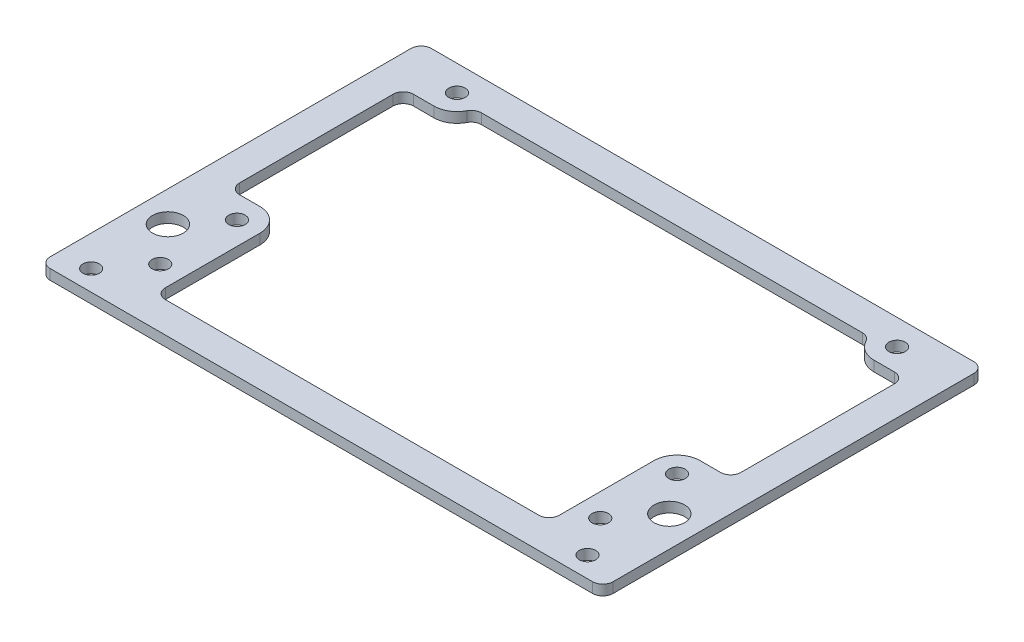
SolidWorks part; units mm, degrees
material "Thornel Mat VMA"
ref_plane "前视基准面" through (0, 0, 0) normal (0, 0, 1) x (1, 0, 0)
ref_plane "上视基准面" through (0, 0, 0) normal (0, 1, 0) x (1, 0, 0)
ref_plane "右视基准面" through (0, 0, 0) normal (1, 0, 0) x (0, 0, -1)
other "Configuration Table"
sketch "草图1" plane through (0, 0, 0) normal (0, 1, 0) x (1, 0, 0)
  line L1 (-43, 29) -> (43, 29) construction
  line L2 (-43, 29) -> (-43, -29) construction
  line L3 (-43, -29) -> (43, -29) construction
  line L4 (43, 29) -> (43, -29) construction
  line L5 (-43, 29) -> (43, -29) construction
  line L6 (-43, -29) -> (43, 29) construction
  line L7 (-55, 39.5) -> (55, 39.5)
  line L8 (-55, 39.5) -> (-55, -39.5)
  line L9 (-55, -39.5) -> (55, -39.5)
  line L10 (55, 39.5) -> (55, -39.5)
  line L11 (-55, 39.5) -> (55, -39.5) construction
  line L12 (-55, -39.5) -> (55, 39.5) construction
  circle A0 centre (43, -29) radius 1.6
  circle A1 centre (-43, -29) radius 1.6
  circle A2 centre (-43, 29) radius 1.6
  circle A3 centre (43, 29) radius 1.6
  circle A4 centre (43, -14) radius 1.6
  circle A5 centre (-43, -14) radius 1.6
  point P0 (0, 0)
  point P10 (0, 0)
  dimension "D3" = 3.2
  dimension "D1" = 86
  dimension "D2" = 58
  dimension "D4" = 110
  dimension "D5" = 79
  dimension "D6" = 43
extrude "凸台-拉伸1" add sketch "草图1" along normal blind 2
sketch "草图3" plane through (0, 2, 0) normal (0, 1, 0) x (1, 0, 0)
  line L1 (-55, -39.5) -> (55, -39.5)
  line L2 (-55, -39.5) -> (-55, -40.5)
  line L3 (-55, -40.5) -> (55, -40.5)
  line L4 (55, -39.5) -> (55, -40.5)
  dimension "D1" = 1
extrude "凸台-拉伸2" add sketch "草图3" against normal blind 2
sketch "草图4" plane through (0, 2, 0) normal (0, 1, 0) x (1, 0, 0)
  line L0 (-55, -40.5) -> (55, -40.5) construction
  line L1 (55, -40.5) -> (55, 39.5) construction
  circle A0 centre (48, -36.5) radius 1.6
  circle A1 centre (-49, -36.5) radius 1.6
  circle A2 centre (43, -29) radius 1.6 construction
  dimension "D1" = 4
  dimension "D2" = 7
  dimension "D3" = 97
extrude "切除-拉伸2" cut sketch "草图4" against normal blind 2
sketch "草图6" plane through (0, 2, 0) normal (0, 1, 0) x (1, 0, 0)
  line L0 (55, -40.5) -> (55, 39.5) construction
  line L1 (-55, 39.5) -> (55, 39.5)
  line L2 (-55, 39.5) -> (-55, 34)
  line L3 (-55, 34) -> (55, 34)
  line L4 (55, 39.5) -> (55, 34)
  line L5 (-55, -40.5) -> (55, -40.5) construction
  line L6 (-38.6125, 28) -> (38.6125, 28)
  line L7 (-49, 24.5) -> (-49, -9.5)
  line L8 (-38.5, -34.5) -> (38.5, -34.5)
  line L9 (49, 24.5) -> (49, -9.5)
  line L10 (-55, 39.5) -> (-55, -40.5) construction
  line L11 (38.5, -14) -> (38.5, -34.5)
  line L13 (43, -9.5) -> (49, -9.5)
  line L14 (-38.5, -14) -> (-38.5, -34.5)
  line L15 (-43, -9.5) -> (-49, -9.5)
  line L16 (-43, 24.5) -> (-49, 24.5)
  line L17 (43, 24.5) -> (49, 24.5)
  arc A1 (-38.5, -14) -> (-43, -9.5) centre (-43, -14) ccw
  arc A2 (43, -9.5) -> (38.5, -14) centre (43, -14) ccw
  arc A3 (38.6125, 28) -> (43, 24.5) centre (43, 29) ccw
  arc A4 (-43, 24.5) -> (-38.6125, 28) centre (-43, 29) ccw
  dimension "D6" = 9
  dimension "D1" = 5
  dimension "D2" = 6
  dimension "D3" = 6
  dimension "D4" = 6
  dimension "D5" = 6
extrude "切除-拉伸4" cut sketch "草图6" against normal blind 2
sketch "草图7" plane through (0, 2, 0) normal (0, 1, 0) x (1, 0, 0)
  line L0 (43, -29) -> (43, -14) construction
  line L2 (38.5, -34.5) -> (55, -34.5) construction
  line L3 (55, -40.5) -> (55, 34) construction
  line L4 (0, -9.6516) -> (0, 0) construction
  circle A0 centre (49, -21.5) radius 3
  circle A1 centre (-49, -21.5) radius 3
  point P7 (43, -21.5)
  dimension "D2" = 6
  dimension "D1" = 6
extrude "切除-拉伸5" cut sketch "草图7" against normal blind 2
fillet "圆角2" radius 2 12 edges at (55, 1, 40.5) (55, 1, -34) (-55, 1, -34) (38.5, 1, 34.5) (-38.5, 1, 34.5) (-49, 1, 9.5) (-49, 1, -24.5) (-38.6125, 1, -28) (38.6125, 1, -28) (49, 1, -24.5) (49, 1, 9.5) (-55, 1, 40.5)
